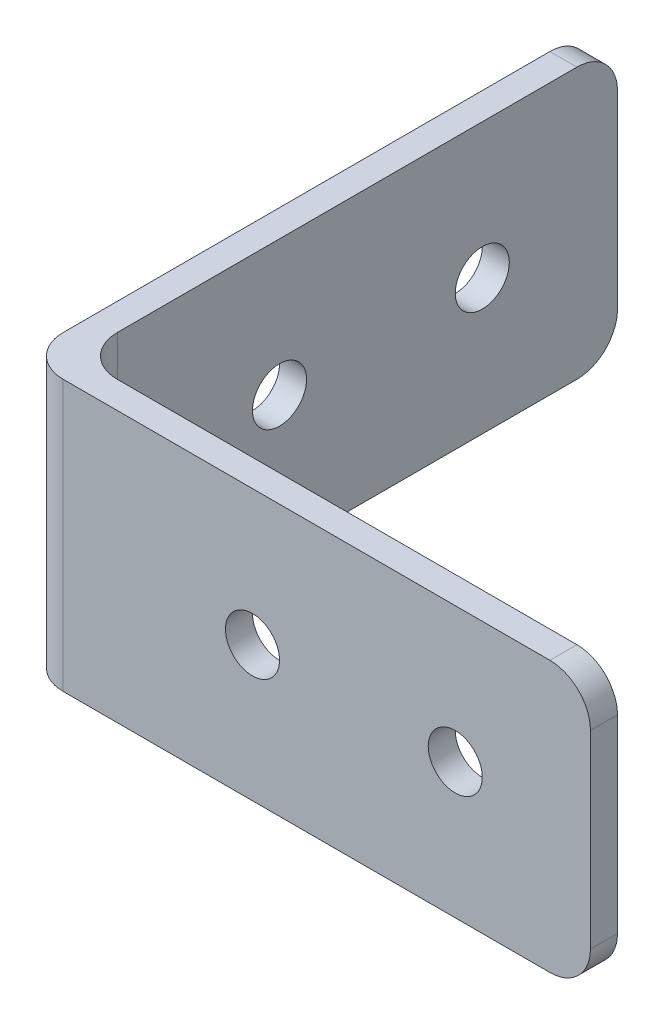
SolidWorks part; units mm, degrees
material "AISI 321 Annealed Stainless Steel (SS)"
ref_plane "Front Plane" through (0, 0, 0) normal (0, 0, 1) x (1, 0, 0)
ref_plane "Top Plane" through (0, 0, 0) normal (0, 1, 0) x (1, 0, 0)
ref_plane "Right Plane" through (0, 0, 0) normal (1, 0, 0) x (0, 0, -1)
sketch "Sketch1" plane through (0, 0, 0) normal (0, 1, 0) x (1, 0, 0)
  line L0 (-13.6449, 18.3551) -> (-13.6449, -21.6449)
  line L1 (-13.6449, -21.6449) -> (26.3551, -21.6449)
  line L2 (26.3551, -21.6449) -> (26.3551, -23.6449)
  line L3 (26.3551, -23.6449) -> (-15.6449, -23.6449)
  line L4 (-15.6449, -23.6449) -> (-15.6449, 18.3551)
  line L5 (-15.6449, 18.3551) -> (-13.6449, 18.3551)
  dimension "D1" = 42
  dimension "D2" = 42
  dimension "D3" = 40
  dimension "D4" = 40
  dimension "D5" = 2
extrude "Boss-Extrude1" add sketch "Sketch1" along normal blind 20
fillet "Fillet1" radius 3 6 edges at (-13.6449, 10, 21.6449) (-15.6449, 10, 23.6449) (26.3551, 20, 22.6449) (26.3551, 0, 22.6449) (-14.6449, 0, -18.3551) (-14.6449, 20, -18.3551)
sketch "Sketch3" plane through (0, 0, 21.6449) normal (0, 0, -1) x (-1, 0, 0)
  line L0 (-26.3551, 10) -> (10.6449, 10) construction
  line L1 (-26.3551, 17) -> (-26.3551, 3) construction
  line L2 (10.6449, 0) -> (10.6449, 20) construction
  circle A0 centre (-1.3551, 10) radius 2
  circle A1 centre (-16.3551, 10) radius 2
  dimension "D1" = 4
  dimension "D2" = 4
  dimension "D3" = 10
  dimension "D4" = 15
sketch "Sketch4" plane through (-13.6449, 0, 0) normal (1, 0, 0) x (0, 0, -1)
  line L0 (-18.6449, 10) -> (18.3551, 10) construction
  line L3 (18.3551, 17) -> (18.3551, 3) construction
  line L4 (-18.6449, 20) -> (-18.6449, 0) construction
  circle A0 centre (8.3551, 10) radius 2
  circle A1 centre (-6.6449, 10) radius 2
  dimension "D1" = 4
  dimension "D2" = 4
  dimension "D3" = 10
  dimension "D4" = 15
extrude "Cut-Extrude1" cut sketch "Sketch3" against normal through all
extrude "Cut-Extrude2" cut sketch "Sketch4" against normal through all
